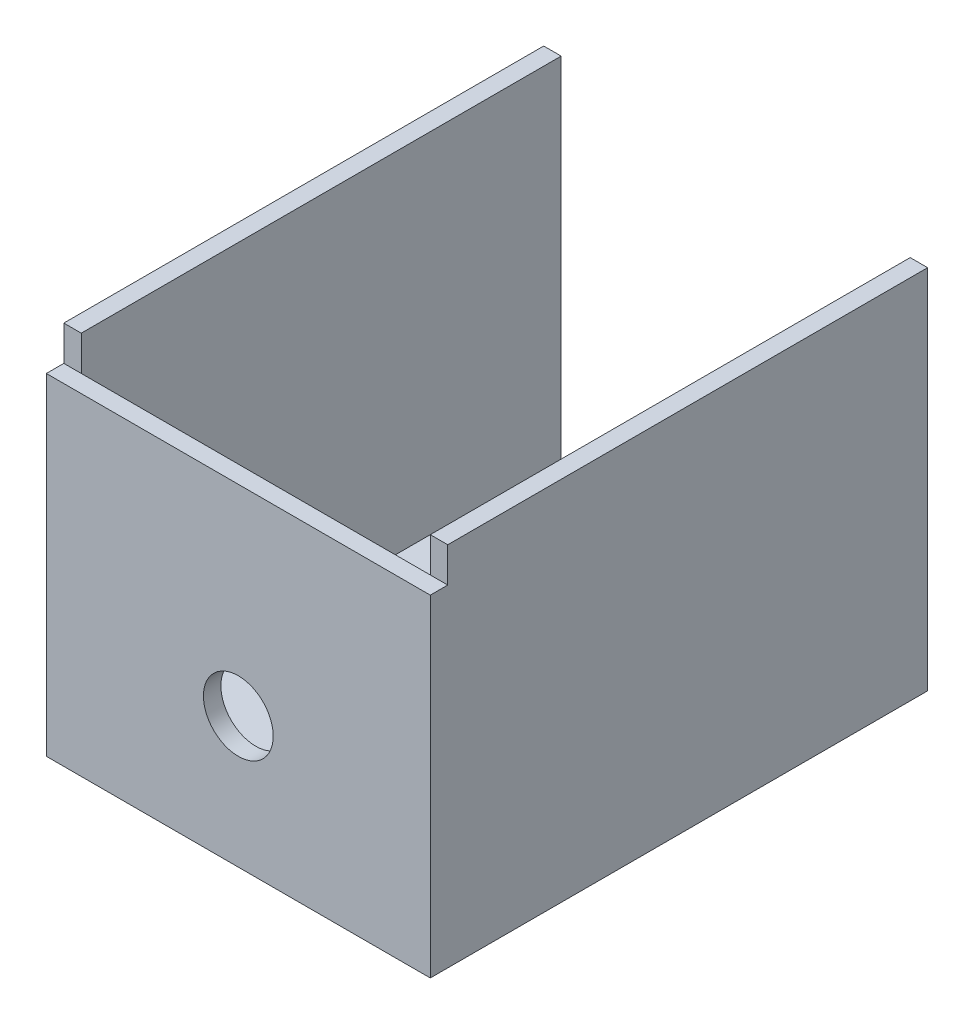
SolidWorks part; units mm, degrees
ref_plane "Front Plane" through (0, 0, 0) normal (0, 0, 1) x (1, 0, 0)
ref_plane "Top Plane" through (0, 0, 0) normal (0, 1, 0) x (1, 0, 0)
ref_plane "Right Plane" through (0, 0, 0) normal (1, 0, 0) x (0, 0, -1)
sketch "Sketch1" plane through (0, 0, 0) normal (0, 0, 1) x (1, 0, 0)
  line L0 (0, 0) -> (0, -42)
  line L1 (0, -42) -> (-44, -42)
  line L2 (-44, -42) -> (-44, 0)
  line L3 (-2, 0) -> (-2, -40)
  line L4 (-2, -40) -> (-42, -40)
  line L5 (-42, -40) -> (-42, 0)
  line L6 (-2, 0) -> (0, 0)
  line L7 (-44, 0) -> (-42, 0)
  dimension "D1" = 44
  dimension "D2" = 42
  dimension "D3" = 2
extrude "Boss-Extrude1" add sketch "Sketch1" along normal blind 55
sketch "Sketch4" plane through (0, -40, 0) normal (0, 1, 0) x (1, 0, 0)
  line L0 (0, -55) -> (0, 0) construction
  line L1 (0, -15.3512) -> (-44, -15.3512)
  line L2 (0, -15.3512) -> (0, -17.3512)
  line L3 (0, -17.3512) -> (-44, -17.3512)
  line L4 (-44, -15.3512) -> (-44, -17.3512)
  line L5 (-44, -55) -> (-44, 0) construction
  line L7 (0, -38.9438) -> (-44, -38.9438)
  line L8 (0, -38.9438) -> (0, -40.9438)
  line L9 (0, -40.9438) -> (-44, -40.9438)
  line L10 (-44, -38.9438) -> (-44, -40.9438)
  dimension "D1" = 2
  dimension "D2" = 2
sketch "Sketch2" plane through (0, 0, 55) normal (0, 0, 1) x (1, 0, 0)
  line L0 (-44, -42) -> (0, -42) construction
  line L1 (0, -42) -> (-44, -42)
  line L2 (0, -42) -> (0, -4)
  line L3 (0, -4) -> (-44, -4)
  line L4 (-44, -42) -> (-44, -4)
  line L5 (-44, 0) -> (-44, -42) construction
  line L6 (-42, -4) -> (-2, -4) construction
extrude "Boss-Extrude2" add sketch "Sketch2" along normal blind 2
sketch "Sketch3" plane through (0, 0, 57) normal (0, 0, 1) x (1, 0, 0)
  circle A0 centre (-22, -27) radius 4
extrude "Cut-Extrude1" cut sketch "Sketch3" against normal through all both and the other way through all
